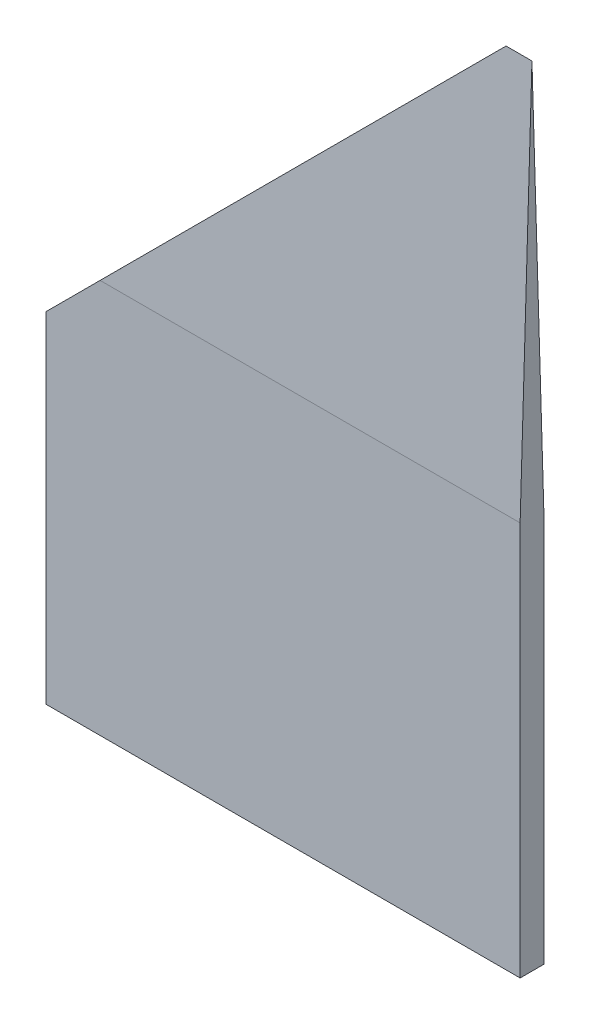
SolidWorks part; units mm, degrees
ref_plane "Front Plane" through (0, 0, 0) normal (0, 0, 1) x (1, 0, 0)
ref_plane "Top Plane" through (0, 0, 0) normal (0, 1, 0) x (1, 0, 0)
ref_plane "Right Plane" through (0, 0, 0) normal (1, 0, 0) x (0, 0, -1)
sketch "Sketch1" plane through (0, 0, 0) normal (0, 1, 0) x (1, 0, 0)
  circle A0 centre (0, 0) radius 25.5
  circle A1 centre (0, 0) radius 27.5
  dimension "D1" = 55
  dimension "D2" = 51
sketch "Sketch2" plane through (0, 0, 0) normal (0, 0, 1) x (1, 0, 0)
  line L0 (-30.2798, 84.6301) -> (-78.3798, 36.5301)
  line L1 (-27.5, 0) -> (-78.3798, 0)
  line L2 (-27.5, 0) -> (-27.5, 84.6301)
  line L3 (-27.5, 84.6301) -> (-30.2798, 84.6301)
  line L4 (-78.3798, 0) -> (-78.3798, 36.5301)
  point P1 (-78.3798, 84.6301)
extrude "Boss-Extrude2" add sketch "Sketch2" along normal mid plane 2.54 separate body
sketch "Sketch3" plane through (0, 0, 0) normal (1, 0, 0) x (0, 0, -1)
  line L0 (0, 84.6301) -> (-1.27, 42.315)
  line L1 (-1.27, 84.6301) -> (1.27, 84.6301) construction
  line L2 (-1.27, 0) -> (-1.27, 84.6301) construction
  line L3 (-1.27, 42.315) -> (-13.7109, 42.315)
  line L4 (-13.7109, 42.315) -> (-13.7109, 86.8321)
  line L5 (-13.7109, 86.8321) -> (21.3053, 86.8321)
  line L6 (21.3053, 42.315) -> (1.27, 42.315)
  line L7 (1.27, 0) -> (1.27, 84.6301) construction
  line L8 (1.27, 42.315) -> (0, 84.6301)
  line L9 (21.3053, 86.8321) -> (21.3053, 42.315)
extrude "Cut-Extrude1" cut sketch "Sketch3" against normal blind 100.076
